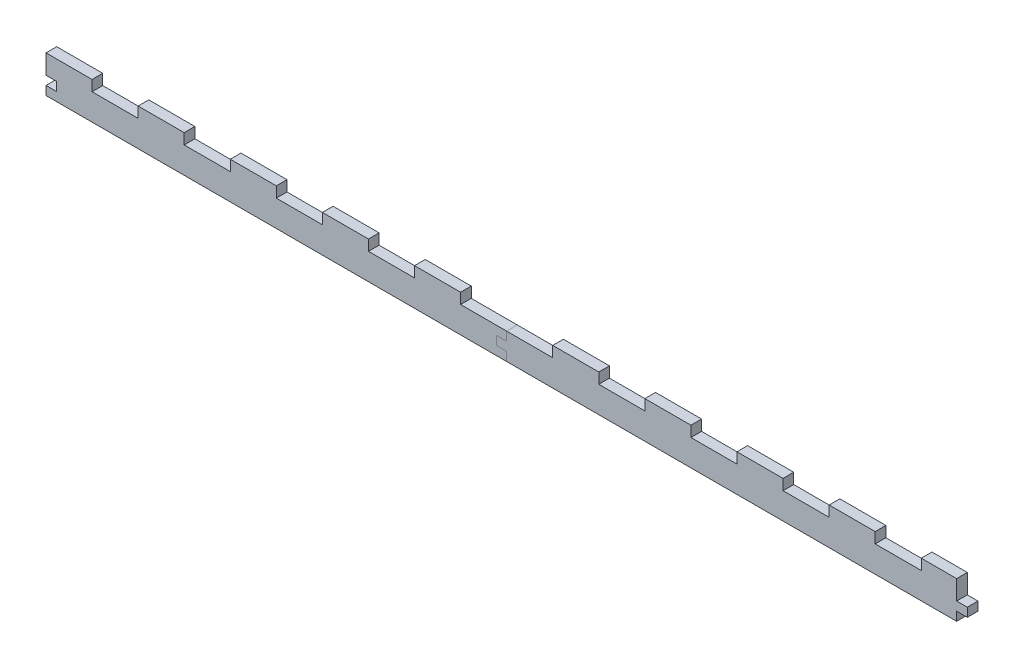
SolidWorks part; units mm, degrees
ref_plane "Front Plane" through (0, 0, 0) normal (0, 0, 1) x (1, 0, 0)
ref_plane "Top Plane" through (0, 0, 0) normal (0, 1, 0) x (1, 0, 0)
ref_plane "Right Plane" through (0, 0, 0) normal (1, 0, 0) x (0, 0, -1)
sketch "Sketch1" plane through (0, 0, 0) normal (0, 0, 1) x (1, 0, 0)
  line L1 (0, 0) -> (444.5, 0)
  line L2 (0, 0) -> (0, 12.7)
  line L3 (0, 12.7) -> (444.5, 12.7)
  line L4 (444.5, 0) -> (444.5, 12.7)
  dimension "D1" = 444.5
  dimension "D2" = 12.7
extrude "Boss-Extrude1" add sketch "Sketch1" along normal blind 5.15
sketch "Sketch2" plane through (0, 0, 5.15) normal (0, 0, 1) x (1, 0, 0)
  line L0 (22.225, 17.85) -> (44.45, 17.85) construction
  line L1 (0, 12.7) -> (22.225, 12.7)
  line L2 (0, 12.7) -> (0, 17.85)
  line L3 (0, 17.85) -> (22.225, 17.85)
  line L4 (22.225, 12.7) -> (22.225, 17.85)
  line L5 (44.45, 12.7) -> (66.675, 12.7)
  line L6 (44.45, 12.7) -> (44.45, 17.85)
  line L7 (44.45, 17.85) -> (66.675, 17.85)
  line L8 (66.675, 12.7) -> (66.675, 17.85)
  line L9 (66.675, 17.85) -> (88.9, 17.85) construction
  line L10 (88.9, 12.7) -> (111.125, 12.7)
  line L11 (88.9, 12.7) -> (88.9, 17.85)
  line L12 (88.9, 17.85) -> (111.125, 17.85)
  line L13 (111.125, 12.7) -> (111.125, 17.85)
  line L14 (111.125, 17.85) -> (133.35, 17.85) construction
  line L15 (133.35, 12.7) -> (155.575, 12.7)
  line L16 (133.35, 12.7) -> (133.35, 17.85)
  line L17 (133.35, 17.85) -> (155.575, 17.85)
  line L18 (155.575, 12.7) -> (155.575, 17.85)
  line L19 (155.575, 17.85) -> (177.8, 17.85) construction
  line L20 (177.8, 12.7) -> (200.025, 12.7)
  line L21 (177.8, 12.7) -> (177.8, 17.85)
  line L22 (177.8, 17.85) -> (200.025, 17.85)
  line L23 (200.025, 12.7) -> (200.025, 17.85)
  line L24 (200.025, 17.85) -> (222.25, 17.85) construction
  line L25 (222.25, 0) -> (222.25, 12.7) construction
  line L26 (0, 0) -> (444.5, 0) construction
  line L27 (444.5, 12.7) -> (0, 12.7) construction
  line L28 (288.925, 17.85) -> (266.7, 17.85) construction
  line L29 (333.375, 17.85) -> (311.15, 17.85) construction
  line L30 (377.825, 17.85) -> (355.6, 17.85) construction
  line L31 (422.275, 17.85) -> (400.05, 17.85) construction
  line L32 (244.475, 12.7) -> (244.475, 17.85)
  line L33 (266.7, 17.85) -> (244.475, 17.85)
  line L34 (266.7, 12.7) -> (266.7, 17.85)
  line L35 (266.7, 12.7) -> (244.475, 12.7)
  line L36 (288.925, 12.7) -> (288.925, 17.85)
  line L37 (311.15, 17.85) -> (288.925, 17.85)
  line L38 (311.15, 12.7) -> (311.15, 17.85)
  line L39 (311.15, 12.7) -> (288.925, 12.7)
  line L40 (333.375, 12.7) -> (333.375, 17.85)
  line L41 (355.6, 17.85) -> (333.375, 17.85)
  line L42 (355.6, 12.7) -> (355.6, 17.85)
  line L43 (355.6, 12.7) -> (333.375, 12.7)
  line L44 (377.825, 12.7) -> (377.825, 17.85)
  line L45 (400.05, 17.85) -> (377.825, 17.85)
  line L46 (400.05, 12.7) -> (400.05, 17.85)
  line L47 (400.05, 12.7) -> (377.825, 12.7)
  line L48 (422.275, 12.7) -> (422.275, 17.85)
  line L49 (444.5, 17.85) -> (422.275, 17.85)
  line L50 (444.5, 12.7) -> (444.5, 17.85)
  line L51 (444.5, 12.7) -> (422.275, 12.7)
  line L52 (200.025, 17.85) -> (222.25, 17.85) construction
  line L53 (222.25, 17.85) -> (244.475, 17.85) construction
  point P4 (0, 0)
  dimension "D2" = 5.15
  dimension "D1" = 5
extrude "Boss-Extrude2" add sketch "Sketch2" against normal up to surface (5.15 mm away) up to face at (222.25, 6.35, 0)
sketch "Sketch3" plane through (0, 0, 5.15) normal (0, 0, 1) x (1, 0, 0)
  line L5 (0, 17.85) -> (0, 0) construction
  line L6 (0, 8.4667) -> (5.15, 8.4667)
  line L7 (0, 8.4667) -> (0, 4.2333)
  line L8 (0, 4.2333) -> (5.15, 4.2333)
  line L9 (5.15, 8.4667) -> (5.15, 4.2333)
  line L10 (5.15, 8.4667) -> (5.15, 12.7) construction
  line L12 (5.15, 4.2333) -> (5.15, 0) construction
  line L13 (0, 0) -> (444.5, 0) construction
  line L14 (22.225, 12.7) -> (0, 12.7) construction
  line L15 (444.5, 0) -> (444.5, 17.85) construction
  line L16 (444.5, 17.85) -> (439.35, 17.85)
  line L17 (444.5, 17.85) -> (444.5, 8.4667)
  line L18 (444.5, 8.4667) -> (439.35, 8.4667)
  line L19 (439.35, 17.85) -> (439.35, 8.4667)
  line L20 (439.35, 4.2333) -> (439.35, 8.4667) construction
  line L21 (444.5, 4.2333) -> (439.35, 4.2333)
  line L22 (444.5, 4.2333) -> (444.5, 0)
  line L23 (444.5, 0) -> (439.35, 0)
  line L24 (439.35, 4.2333) -> (439.35, 0)
  dimension "D1" = 5.15
extrude "Cut-Extrude1" cut sketch "Sketch3" against normal through all
sketch "Sketch4" plane through (0, 0, 5.15) normal (0, 0, 1) x (1, 0, 0)
  line L0 (222.25, 12.7) -> (222.25, 8.4667)
  line L1 (244.475, 12.7) -> (200.025, 12.7) construction
  line L2 (222.25, 8.4667) -> (217.25, 8.4667)
  line L3 (217.25, 8.4667) -> (217.25, 4.2333)
  line L4 (217.25, 4.2333) -> (222.25, 4.2333)
  line L5 (222.25, 4.2333) -> (222.25, 0)
  line L6 (0, 0) -> (439.35, 0) construction
  point P10 (216.5184, 8.4667)
  dimension "D1" = 5
split "Split1" trim tools "Sketch4" bodies to split 103 resulting bodies 104 105
equation "\"standard_thickness\"= 5.15mm"
equation "\"D1@Boss-Extrude1\"=\"standard_thickness\""
equation "\"D2@Sketch2\"=\"standard_thickness\""
equation "\"D1@Sketch3\"=\"standard_thickness\""
